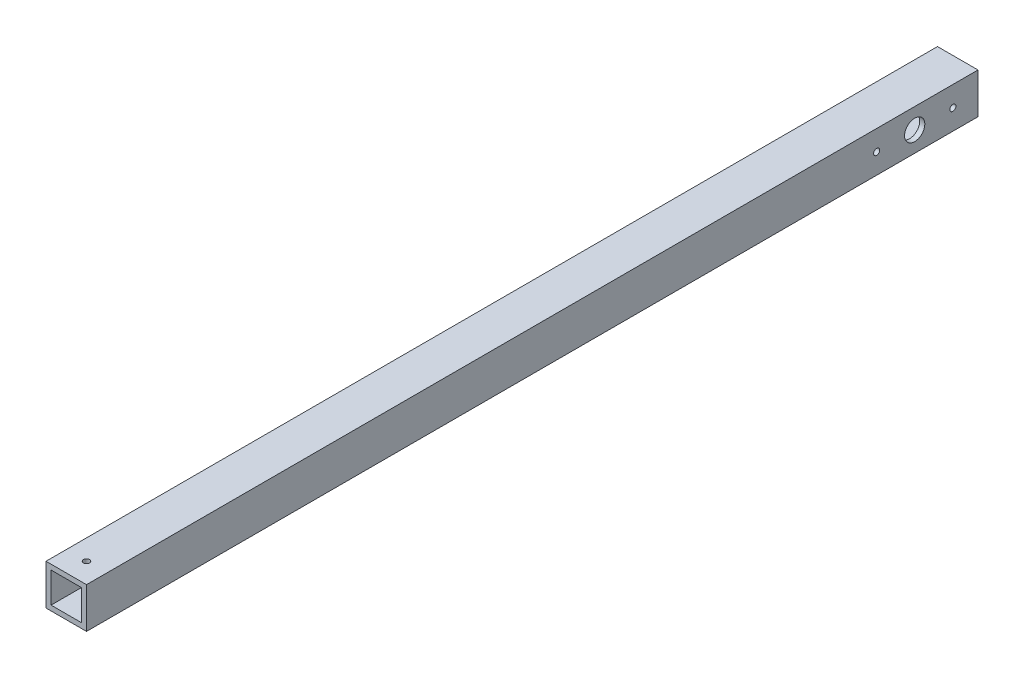
SolidWorks part; units mm, degrees
material "6061-T6 (SS)"
ref_plane "Front Plane" through (0, 0, 0) normal (0, 0, 1) x (1, 0, 0)
ref_plane "Top Plane" through (0, 0, 0) normal (0, 1, 0) x (1, 0, 0)
ref_plane "Right Plane" through (0, 0, 0) normal (1, 0, 0) x (0, 0, -1)
sketch "Sketch1" plane through (0, 0, 0) normal (0, 0, 1) x (1, 0, 0)
  line L0 (-9.525, 9.525) -> (9.525, 9.525)
  line L1 (-12.7, 12.7) -> (12.7, 12.7)
  line L2 (-12.7, 12.7) -> (-12.7, -12.7)
  line L3 (-12.7, -12.7) -> (12.7, -12.7)
  line L4 (12.7, 12.7) -> (12.7, -12.7)
  line L5 (-12.7, 12.7) -> (12.7, -12.7) construction
  line L6 (-12.7, -12.7) -> (12.7, 12.7) construction
  line L7 (9.525, 9.525) -> (9.525, -9.525)
  line L8 (-9.525, -9.525) -> (9.525, -9.525)
  line L9 (-9.525, 9.525) -> (-9.525, -9.525)
  point P0 (0, 0)
  dimension "D1" = 25.4
  dimension "D2" = 25.4
  dimension "D3" = 3.175
extrude "Boss-Extrude1" add sketch "Sketch1" along normal mid plane 558.8
sketch "Sketch7" plane through (0, 12.7, 0) normal (0, 1, 0) x (1, 0, 0)
  line L0 (-12.7, -279.4) -> (-12.7, 279.4) construction
  line L2 (12.7, -279.4) -> (-12.7, -279.4) construction
  circle A0 centre (0, -266.7) radius 1.905
  point P4 (0, -279.4)
  dimension "D1" = 3.81
  dimension "D2" = 12.7
  dimension "D3" = 12.7
extrude "Cut-Extrude1" cut sketch "Sketch7" against normal through all
sketch "Sketch8" plane through (12.7, 0, 0) normal (1, 0, 0) x (0, 0, -1)
  line L0 (279.4, -12.7) -> (279.4, 12.7) construction
  line L1 (-279.4, 12.7) -> (279.4, 12.7) construction
  circle A0 centre (215.9, 0) radius 1.905
  circle A1 centre (263.652, 0) radius 1.905
  circle A2 centre (239.7125, 0) radius 6.35
  dimension "D1" = 3.81
  dimension "D4" = 12.7
  dimension "D3" = 63.5
  dimension "D5" = 12.7
  dimension "D8" = 23.8125
  dimension "D2" = 2
extrude "Cut-Extrude2" cut sketch "Sketch8" against normal through all
